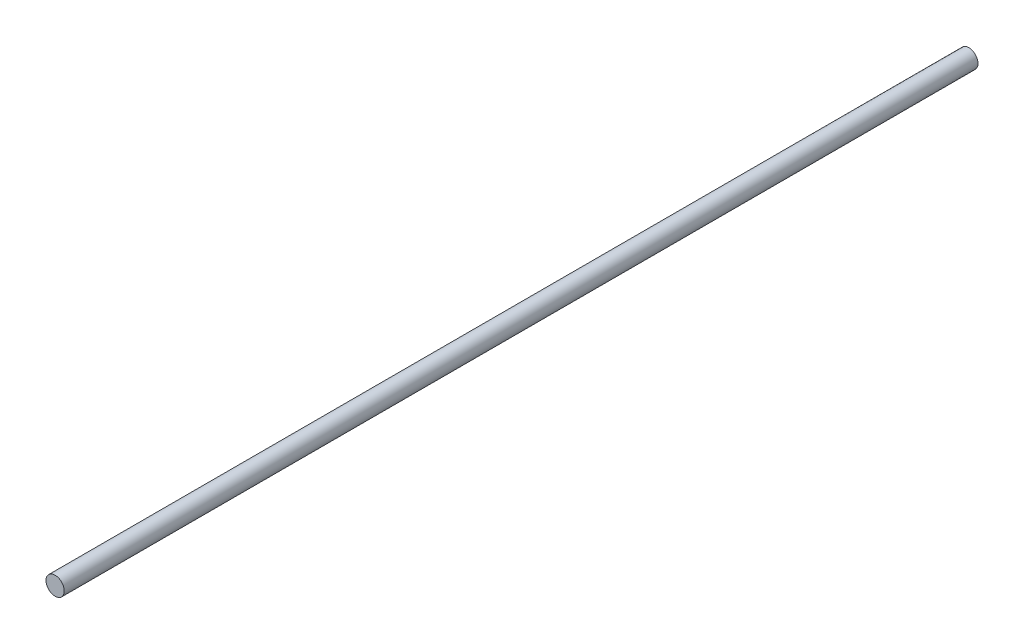
SolidWorks part; units mm, degrees
ref_plane "前基準面" through (0, 0, 0) normal (0, 0, 1) x (1, 0, 0)
ref_plane "上基準面" through (0, 0, 0) normal (0, 1, 0) x (1, 0, 0)
ref_plane "右基準面" through (0, 0, 0) normal (1, 0, 0) x (0, 0, -1)
sketch "草圖1" plane through (0, 0, 0) normal (0, 0, 1) x (1, 0, 0)
  circle A0 centre (0, 0) radius 4
  dimension "D1" = 8
extrude "填料-伸長1" add sketch "草圖1" along normal blind 400
